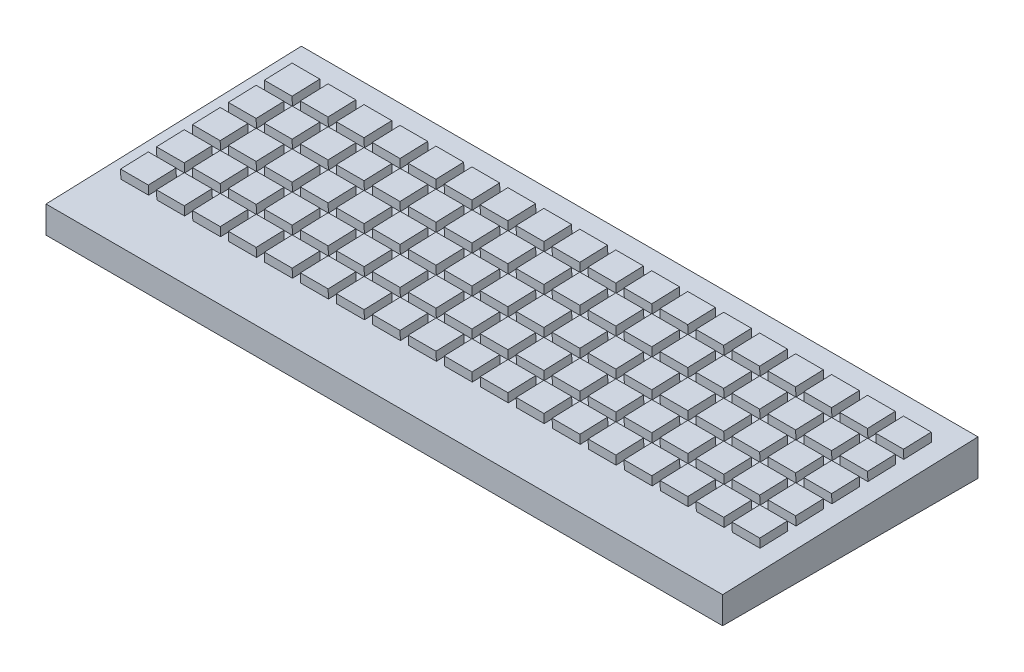
SolidWorks part; units mm, degrees
ref_plane "Front Plane" through (0, 0, 0) normal (0, 0, 1) x (1, 0, 0)
ref_plane "Top Plane" through (0, 0, 0) normal (0, 1, 0) x (1, 0, 0)
ref_plane "Right Plane" through (0, 0, 0) normal (1, 0, 0) x (0, 0, -1)
sketch "Sketch1" plane through (0, 0, 0) normal (1, 0, 0) x (0, 0, -1)
  line L0 (-142, 0) -> (0, 0)
  line L1 (0, 0) -> (0, 20)
  line L2 (0, 20) -> (-142, 15)
  line L3 (-142, 15) -> (-142, 0)
  point P3 (0, 0)
  point P6 (4.5735, 0)
  point P7 (0, 0)
  point P8 (0, 0)
  point P9 (0, 0)
  point P10 (0, 0)
  dimension "D1" = 20
  dimension "D2" = 15
  dimension "D3" = 142
extrude "Boss-Extrude1" add sketch "Sketch1" along normal mid plane 376.275
sketch "Sketch2" plane through (0, 19.9752, 0.7034) normal (0, 0.9994, 0.0352) x (1, 0, 0)
  line L0 (-188.1375, 0.7038) -> (-188.1375, -141.3842) construction
  line L1 (-178.1375, -14.2962) -> (178.1375, -14.2962) construction
  line L2 (-178.1375, -14.2962) -> (-178.1375, -129.3842) construction
  line L3 (-178.1375, -129.3842) -> (178.1375, -129.3842) construction
  line L4 (178.1375, -14.2962) -> (178.1375, -129.3842) construction
  line L5 (188.1375, 0.7038) -> (-188.1375, 0.7038) construction
  line L6 (188.1375, -141.3842) -> (-188.1375, -141.3842) construction
  line L7 (188.1375, 0.7038) -> (188.1375, -141.3842) construction
  line L9 (-178.1375, -14.2962) -> (-162.7044, -14.2962)
  line L10 (-178.1375, -14.2962) -> (-178.1375, -29.7293)
  line L11 (-178.1375, -29.7293) -> (-162.7044, -29.7293)
  line L12 (-162.7044, -14.2962) -> (-162.7044, -29.7293)
  dimension "D1" = 10
  dimension "D2" = 15
  dimension "D3" = 12
  dimension "D4" = 10
  dimension "D5" = 15.4331
extrude "Boss-Extrude2" add sketch "Sketch2" along normal mid plane 10 separate body
pattern_linear "LPattern1" count 18 spacing 20 along (1, 0, 0) count 5 spacing 20 along (0, -0.0352, 0.9994) of "Boss-Extrude2"
sketch "Sketch3" plane through (0, 0, 0) normal (0, -1, 0) x (1, 0, 0)
  line L0 (-177.822, 119.3115) -> (176.9269, 119.3115) construction
  line L1 (176.9269, 119.3115) -> (176.9269, 135.5316) construction
  line L2 (176.9269, 135.5316) -> (-177.822, 135.5316) construction
  line L3 (-177.822, 135.5316) -> (-177.822, 119.3115) construction
  line L4 (-172.5822, 119.3115) -> (-164.3659, 135.5316)
  line L5 (-164.3659, 135.5316) -> (-159.0002, 135.5316)
  line L6 (-159.0002, 135.5316) -> (-167.2165, 119.3115)
  line L7 (-167.2165, 119.3115) -> (-172.5822, 119.3115)
extrude "Cut-Extrude1" cut sketch "Sketch3" against normal blind 12
pattern_linear "LPattern2" count 34 spacing 10 along (1, 0, 0) of "Cut-Extrude1"
sketch "Sketch5" plane through (0, 0, 0) normal (0, -1, 0) x (1, 0, 0)
  line L0 (-169.0002, 135.5316) -> (-177.2165, 119.3115)
  line L1 (-169.0002, 135.5316) -> (-174.3659, 135.5316)
  line L2 (-174.3659, 135.5316) -> (-178.1375, 128.086)
  line L3 (-178.1375, 128.086) -> (-178.1375, 119.3115)
  line L4 (-159.0002, 135.5316) -> (-164.3659, 135.5316) construction
  line L5 (-164.3659, 135.5316) -> (-172.5822, 119.3115) construction
  line L6 (-172.5822, 119.3115) -> (-183.1645, 119.3115) construction
  line L7 (-169.0002, 135.5316) -> (-164.3659, 135.5316) construction
  line L8 (-159.0002, 135.5316) -> (-154.3659, 135.5316) construction
  line L9 (-188.1375, 142) -> (-188.1375, 0) construction
  line L10 (-178.1375, 119.3115) -> (-177.2165, 119.3115)
  line L11 (166.9561, 119.3115) -> (175.6341, 135.5316)
  line L12 (175.6341, 135.5316) -> (177.081, 135.5316)
  line L13 (177.081, 128.2069) -> (172.3218, 119.3115)
  line L14 (172.3218, 119.3115) -> (166.9561, 119.3115)
  line L15 (175.6341, 135.5316) -> (170.9998, 135.5316) construction
  line L16 (177.081, 128.2069) -> (177.081, 135.5316)
  dimension "D1" = 10
extrude "Cut-Extrude2" cut sketch "Sketch5" against normal up to surface (12 mm away) up to face at (-165.7912, 12, 127.4215)
